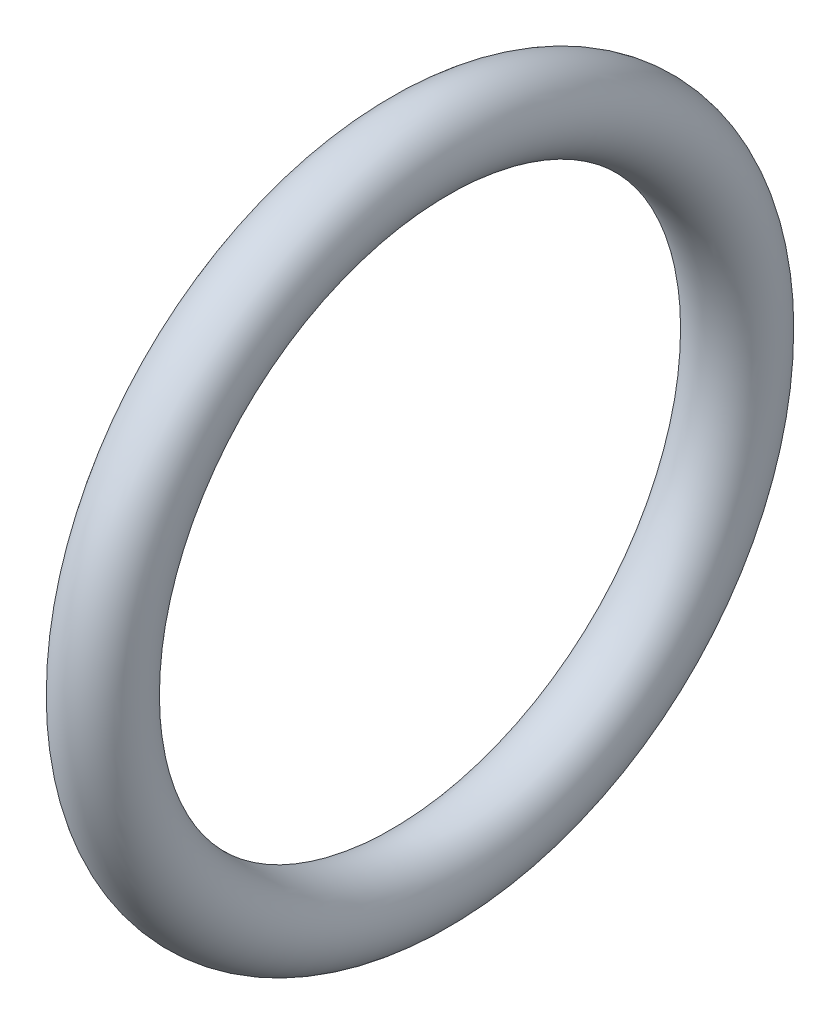
SolidWorks part; units mm, degrees
material "橡胶"
ref_plane "前视基准面" through (0, 0, 0) normal (0, 0, 1) x (1, 0, 0)
ref_plane "上视基准面" through (0, 0, 0) normal (0, 1, 0) x (1, 0, 0)
ref_plane "右视基准面" through (0, 0, 0) normal (1, 0, 0) x (0, 0, -1)
sketch "草图1" plane through (0, 0, 0) normal (0, 0, 1) x (1, 0, 0)
  line L0 (0, 0) -> (0, 10.3)
  line L1 (8.7065, 0) -> (-11.2143, 0)
  circle A0 centre (0, 10.3) radius 1.3
revolve "旋转1" add sketch "草图1" angle 360 about L1
